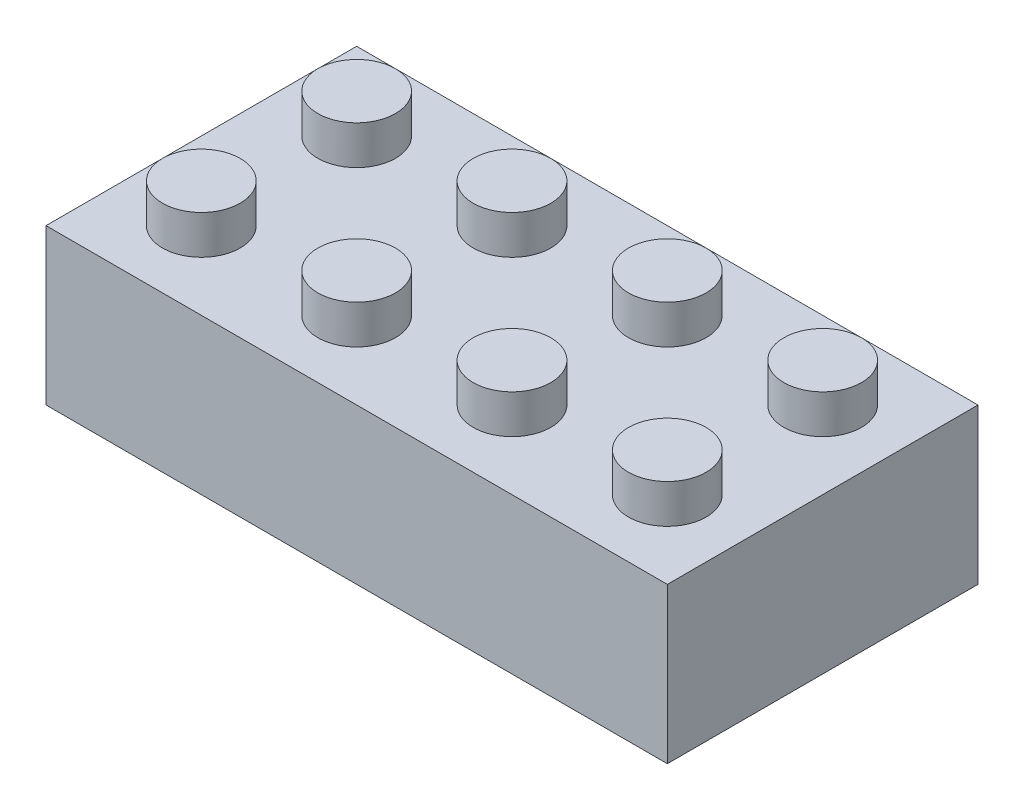
SolidWorks part; units mm, degrees
ref_plane "Front Plane" through (0, 0, 0) normal (0, 0, 1) x (1, 0, 0)
ref_plane "Top Plane" through (0, 0, 0) normal (0, 1, 0) x (1, 0, 0)
ref_plane "Right Plane" through (0, 0, 0) normal (1, 0, 0) x (0, 0, -1)
sketch "Sketch1" plane through (0, 0, 0) normal (0, 1, 0) x (1, 0, 0)
  line L1 (0, 0) -> (20.32, 0)
  line L2 (0, 0) -> (0, 10.16)
  line L3 (0, 10.16) -> (20.32, 10.16)
  line L4 (20.32, 0) -> (20.32, 10.16)
  dimension "D2" = 20.32
extrude "Boss-Extrude1" add sketch "Sketch1" along normal blind 5.08
sketch "Sketch2" plane through (0, 5.08, 0) normal (0, 1, 0) x (1, 0, 0)
  line L0 (0, 0) -> (20.32, 0) construction
  line L1 (0, 10.16) -> (0, 0) construction
  circle A0 centre (2.54, 2.54) radius 1.27
  dimension "D1" = 2.54
  dimension "D2" = 2.54
  dimension "D3" = 2.54
extrude "Boss-Extrude2" add sketch "Sketch2" along normal blind 1.27
pattern_linear "LPattern1" count 4 spacing 5.08 along (1, 0, 0) count 2 spacing 5.08 along (0, 0, -1) of "Boss-Extrude2"
equation "\"X-space\"= int ( ( \"D2@Sketch1\" / 2 ) * 10 )"
equation "\"Y-space\"= int (  ( \"D1@Sketch1\" / 2 )  * 10 ) "
equation "\"D1@LPattern1\"=\"X-space\""
equation "\"D2@LPattern1\"=\"Y-space\""
